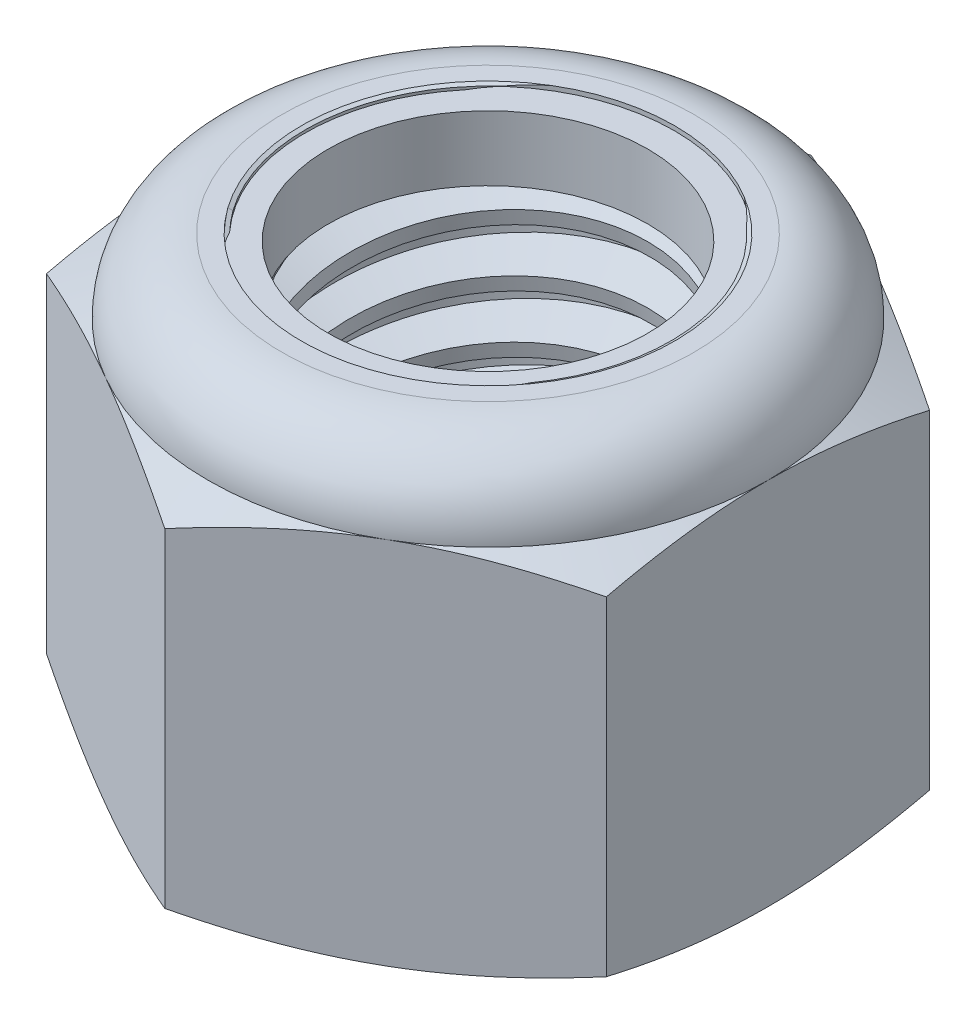
SolidWorks part; units mm, degrees
ref_plane "Front" through (0, 0, 0) normal (0, 0, 1) x (1, 0, 0)
ref_plane "Top" through (0, 0, 0) normal (0, 1, 0) x (1, 0, 0)
ref_plane "Right" through (0, 0, 0) normal (1, 0, 0) x (0, 0, -1)
sketch "Sketch1" plane through (0, 0, 0) normal (0, 1, 0) x (1, 0, 0)
  line L1 (0, 10.9985) -> (-9.525, 5.4993)
  line L2 (-9.525, 5.4993) -> (-9.525, -5.4993)
  line L3 (-9.525, -5.4993) -> (0, -10.9985)
  line L4 (0, -10.9985) -> (9.525, -5.4993)
  line L5 (9.525, -5.4993) -> (9.525, 5.4993)
  line L6 (9.525, 5.4993) -> (0, 10.9985)
  circle A0 centre (0, 0) radius 9.525 construction
  dimension "Hex Flats" = 19.05
extrude "Extrude1" add sketch "Sketch1" along normal blind 15.0812
sketch "Sketch2" plane through (0, 0, 0) normal (1, 0, 0) x (0, 0, -1)
  line L0 (-6.35, 0) -> (-6.35, 15.0812) construction
  line L1 (0, 0) -> (6.35, 0)
  line L2 (0, 0) -> (0, 15.0812)
  line L3 (0, 15.0812) -> (6.35, 15.0812)
  line L4 (6.35, 0) -> (6.35, 15.0812)
  line L5 (-5.4993, 15.0812) -> (5.4993, 15.0812) construction
  line L7 (0, -6.35) -> (0, 0) construction
  dimension "Thread Dia" = 12.7
revolve "Revolve1" add sketch "Sketch2" angle 360 about L7
sketch "Sketch3" plane through (0, 0, 0) normal (1, 0, 0) x (0, 0, -1)
  line L0 (6.35, 15.0812) -> (-6.35, 15.0812) construction
  line L1 (-6.35, 15.0812) -> (-6.35, 13.1274) construction
  line L2 (-6.35, 13.1274) -> (6.35, 15.0812) construction
  line L3 (6.35, 15.0812) -> (6.3871, 14.8399) construction
  line L4 (6.3871, 14.8399) -> (6.6471, 13.1501)
  line L5 (6.6471, 13.1501) -> (5.509, 13.5928)
  line L6 (5.509, 13.5928) -> (5.4347, 14.0756)
  line L7 (5.4347, 14.0756) -> (6.3871, 14.8399)
  line L8 (5.4719, 13.8342) -> (6.5171, 13.995) construction
  line L9 (6.35, 15.0812) -> (6.35, 13.9693) construction
  line L10 (6.35, 13.9693) -> (-6.35, 12.0154) construction
  line L11 (-6.35, 12.0154) -> (-6.35, 13.1274) construction
  line L12 (-0.3214, 15.0812) -> (0.3214, 10.9035) construction
  line L13 (-6.35, 0) -> (-6.35, 15.0812) construction
  line L14 (0, 15.0812) -> (6.35, 15.0812) construction
  line L15 (6.35, 0) -> (6.35, 15.0812) construction
  point P13 (0, 12.9924)
  dimension "D1" = 0.2442
  dimension "D2" = 0.4885
  dimension "Thread Pitch" = 1.9538
  dimension "D4" = 60
  dimension "D5" = 1.9538
revolve "Cut-Revolve1" cut sketch "Sketch3" angle 360 about L12
pattern_linear "LPattern1" count 8 spacing 1.9538 along (0, -1, 0) count 2 spacing 1.9538 along (0, 1, 0) of "Cut-Revolve1"
sketch "Sketch4" plane through (0, 0, 0) normal (1, 0, 0) x (0, 0, -1)
  line L0 (0, 15.0812) -> (6.35, 15.0812)
  line L1 (6.35, 15.0812) -> (5.4347, 14.6545)
  line L2 (5.4347, 14.6545) -> (5.4347, 0.4268)
  line L3 (5.4347, 0.4268) -> (6.35, 0)
  line L4 (6.35, 0) -> (0, 0)
  line L5 (0, 0) -> (0, 15.0812)
  line L6 (6.35, 0) -> (6.35, 15.0812) construction
  line L7 (0, 15.0812) -> (6.35, 15.0812) construction
  line L8 (0, 0) -> (6.35, 0) construction
  line L9 (0, 0) -> (0, 15.0812) construction
  line L10 (0, 15.0812) -> (0, 16.0911) construction
  dimension "D1" = 25
revolve "Cut-Revolve2" cut sketch "Sketch4" angle 360 about L10
combine bodies "Combine1" operation type subtract main body 112 bodies to subtract 111
sketch "Sketch5" plane through (0, 0, 0) normal (1, 0, 0) x (0, 0, -1)
  line L0 (0, 0) -> (9.525, 0)
  line L1 (9.525, 0) -> (10.9985, 0.6871)
  line L2 (10.9985, 0.6871) -> (10.9985, 11.8806)
  line L3 (10.9985, 11.8806) -> (9.525, 12.5677)
  line L4 (7.0115, 15.0813) -> (7.0115, 16.3513)
  line L5 (7.0115, 16.3513) -> (12.2685, 16.3513)
  line L6 (12.2685, 16.3513) -> (12.2685, -1.27)
  line L7 (12.2685, -1.27) -> (0, -1.27)
  line L8 (0, -1.27) -> (0, 0)
  line L9 (9.525, 12.5677) -> (9.525, 0) construction
  line L10 (0, 0) -> (6.35, 0) construction
  line L13 (10.9985, 6.2839) -> (12.2685, 6.2839) construction
  line L14 (10.9985, 15.0812) -> (10.9985, 0) construction
  line L15 (0, 0) -> (0, 16.3513) construction
  line L20 (0, 16.3513) -> (7.0115, 16.3513) construction
  line L22 (0, 15.0812) -> (6.35, 15.0812) construction
  arc A0 (9.525, 12.5677) -> (7.0115, 15.0813) centre (7.0115, 12.5677) ccw
  dimension "D1" = 25
  dimension "D2" = 1.27
  dimension "D3" = 15.0813
  dimension "D4" = 2.5135
revolve "Cut-Revolve3" cut sketch "Sketch5" angle 360 about L15
sketch "Sketch6" plane through (0, 0, 0) normal (1, 0, 0) x (0, 0, -1)
  line L0 (0, 12.5677) -> (9.3726, 12.5677)
  line L1 (7.0115, 14.9289) -> (6.2231, 14.9289)
  line L2 (0, 16.3513) -> (0, 12.5677)
  line L3 (6.2231, 16.3513) -> (0, 16.3513)
  line L4 (0, 16.3513) -> (7.0115, 16.3513) construction
  line L5 (0, 0) -> (0, 16.3513) construction
  line L6 (0, 16.3513) -> (0, 44.323) construction
  line L7 (6.2231, 14.9289) -> (6.2231, 16.3513)
  line L8 (7.0115, 15.0813) -> (7.0115, 14.9289) construction
  line L9 (6.2231, 14.9289) -> (5.4347, 14.9289) construction
  line L10 (5.4347, 14.9289) -> (5.4347, 14.6545) construction
  arc A0 (9.3726, 12.5677) -> (7.0115, 14.9289) centre (7.0115, 12.5677) ccw
  arc A1 (9.525, 12.5677) -> (7.0115, 15.0813) centre (7.0115, 12.5677) ccw construction
  dimension "D1" = 0.1524
revolve "Cut-Revolve4" cut sketch "Sketch6" angle 360 about L6
sketch "Sketch7" plane through (0, 0, 0) normal (1, 0, 0) x (0, 0, -1)
  line L0 (5.4347, 12.6439) -> (9.2951, 12.6439)
  line L1 (7.0115, 14.8527) -> (5.4347, 14.8527)
  line L2 (5.4347, 14.8527) -> (5.4347, 12.6439)
  line L3 (5.4347, 12.6439) -> (0, 12.6439) construction
  line L4 (0, 12.6439) -> (0, 14.8527) construction
  line L5 (0, 14.8527) -> (5.4347, 14.8527) construction
  line L6 (5.4347, 12.6439) -> (5.4347, 12.5677) construction
  line L7 (0, 12.5677) -> (9.3726, 12.5677) construction
  line L8 (7.0115, 14.8527) -> (7.0115, 14.9289) construction
  arc A0 (9.2951, 12.6439) -> (7.0115, 14.8527) centre (7.0115, 12.5677) ccw
  arc A2 (9.3726, 12.5677) -> (7.0115, 14.9289) centre (7.0115, 12.5677) ccw construction
  dimension "D1" = 0.0762
revolve "Revolve2" add sketch "Sketch7" angle 360 about L4
equation "\"D1@Sketch3\"=\"Thread Pitch@Sketch3\"/8"
equation "\"D2@Sketch3\"=\"Thread Pitch@Sketch3\"/4"
equation "\"D5@Sketch3\"=\"Thread Pitch@Sketch3\""
equation "\"D4@LPattern1\"=\"Thread Pitch@Sketch3\""
equation "\"D3@LPattern1\"=\"Thread Pitch@Sketch3\""
equation "\"D1@LPattern1\"=\"Height@Extrude1\"/\"Thread Pitch@Sketch3\""
equation "\"D4@Sketch5\"=\"Height@Extrude1\"/6"
